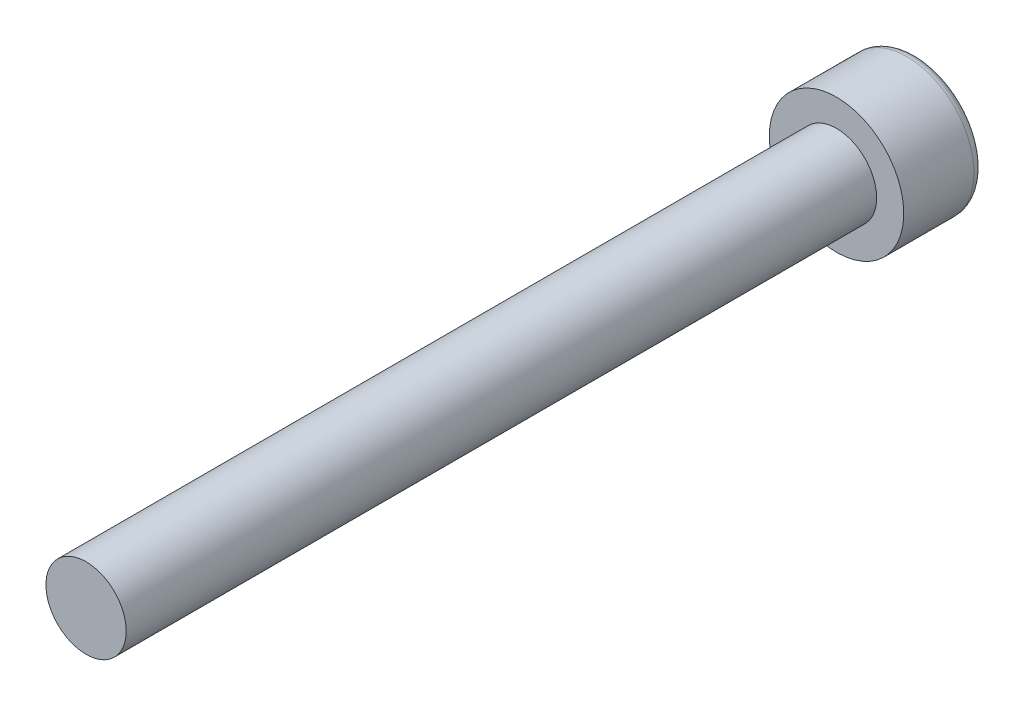
SolidWorks part; units mm, degrees
ref_plane "Alzado" through (0, 0, 0) normal (0, 0, 1) x (1, 0, 0)
ref_plane "Planta" through (0, 0, 0) normal (0, 1, 0) x (1, 0, 0)
ref_plane "Vista lateral" through (0, 0, 0) normal (1, 0, 0) x (0, 0, -1)
sketch "Croquis1" plane through (0, 0, 0) normal (0, 0, 1) x (1, 0, 0)
  circle A0 centre (0, 0) radius 2
  dimension "D1" = 4
extrude "Saliente-Extruir1" add sketch "Croquis1" along normal blind 37.4
sketch "Croquis2" plane through (0, 0, 0) normal (0, 0, -1) x (-1, 0, 0)
  circle A0 centre (0, 0) radius 3.35
  dimension "D1" = 6.7
extrude "Saliente-Extruir2" add sketch "Croquis2" along normal blind 4
sketch "Croquis3" plane through (0, 0, -4) normal (0, 0, -1) x (-1, 0, 0)
  line L1 (0, -1.85) -> (1.6021, -0.925)
  line L2 (1.6021, -0.925) -> (1.6021, 0.925)
  line L3 (1.6021, 0.925) -> (0, 1.85)
  line L4 (0, 1.85) -> (-1.6021, 0.925)
  line L5 (-1.6021, 0.925) -> (-1.6021, -0.925)
  line L6 (-1.6021, -0.925) -> (0, -1.85)
  circle A0 centre (0, 0) radius 1.6021 construction
  dimension "D1" = 3.7
extrude "Cortar-Extruir1" cut sketch "Croquis3" against normal blind 2.5
fillet "Redondeo1" radius 0.5 1 edges at (-3.35, 0, -4)
